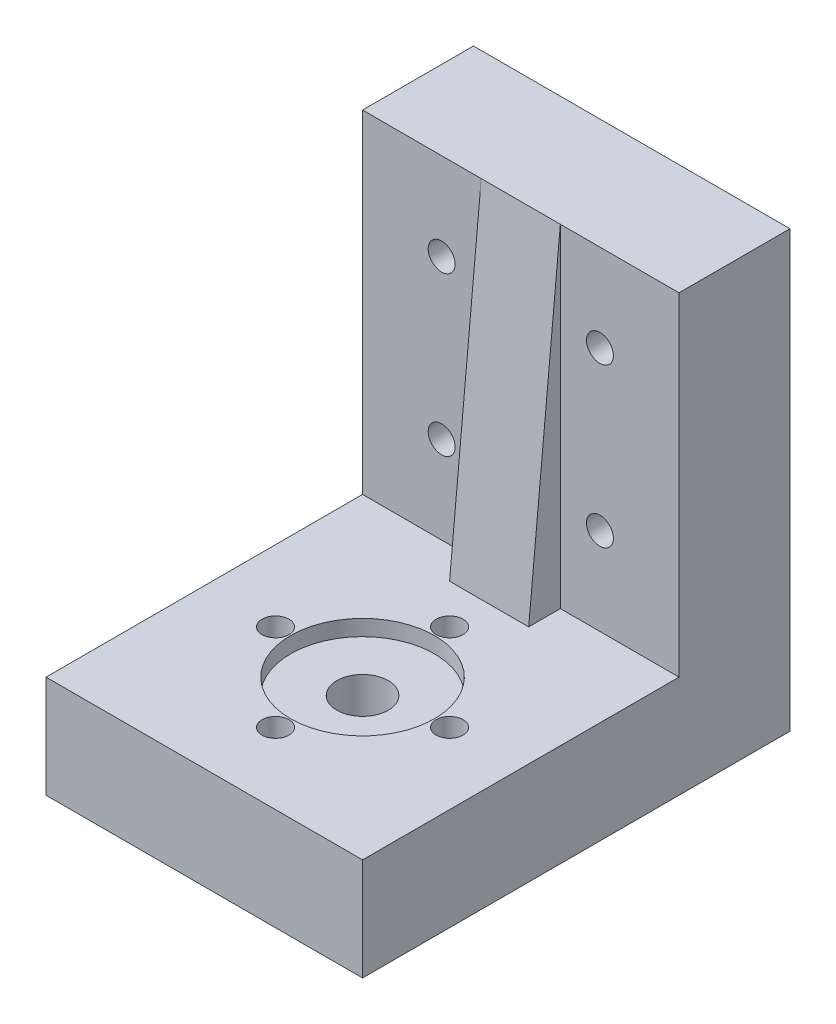
SolidWorks part; units mm, degrees
material "ABS"
ref_plane "Front Plane" through (0, 0, 0) normal (0, 0, 1) x (1, 0, 0)
ref_plane "Top Plane" through (0, 0, 0) normal (0, 1, 0) x (1, 0, 0)
ref_plane "Right Plane" through (0, 0, 0) normal (1, 0, 0) x (0, 0, -1)
sketch "Sketch1" plane through (0, 0, 0) normal (1, 0, 0) x (0, 0, -1)
  line L0 (24.9296, 27.1619) -> (24.9296, -27.8381)
  line L1 (24.9296, -27.8381) -> (-29.0904, -27.8381)
  line L2 (-29.0904, -27.8381) -> (-29.0904, -14.9081)
  line L3 (-29.0904, -14.9081) -> (10.9096, -14.9081)
  line L4 (10.9096, -14.9081) -> (10.9096, 27.1619)
  line L5 (10.9096, 27.1619) -> (24.9296, 27.1619)
  dimension "D1" = 55
  dimension "D2" = 14.02
  dimension "D3" = 12.93
  dimension "D4" = 40
extrude "Boss-Extrude1" add sketch "Sketch1" along normal mid plane 40
sketch "Sketch2" plane through (0, -14.9081, 0) normal (0, 1, 0) x (1, 0, 0)
  line L0 (20, -29.0904) -> (-20, -29.0904) construction
  circle A0 centre (0, -9.0904) radius 3.25
  dimension "D1" = 6.5
  dimension "D2" = 20
  dimension "D3" = 40
extrude "Cut-Extrude1" cut sketch "Sketch2" against normal through all contours A0
sketch "Sketch3" plane through (0, -14.9081, 0) normal (0, 1, 0) x (1, 0, 0)
  circle A0 centre (0, -9.0904) radius 9.1
  dimension "D1" = 18.2
extrude "Cut-Extrude2" cut sketch "Sketch3" against normal blind 2 contours A0
sketch "Sketch4" plane through (0, -14.9081, 0) normal (0, 1, 0) x (1, 0, 0)
  circle A0 centre (0, -9.0904) radius 11 construction
  circle A1 centre (0, 1.9096) radius 1.7
  circle A2 centre (11, -9.0904) radius 1.7
  circle A3 centre (0, -20.0904) radius 1.7
  circle A4 centre (-11, -9.0904) radius 1.7
  dimension "D1" = 22
  dimension "D2" = 3.4
  dimension "D3" = 4
extrude "Cut-Extrude3" cut sketch "Sketch4" against normal through all contours A1 | A2 | A3 | A4
sketch "Sketch5" plane through (0, 0, -10.9096) normal (0, 0, 1) x (1, 0, 0)
  line L0 (0, 27.1619) -> (0, -14.9081) construction
  line L1 (20, 27.1619) -> (-20, 27.1619) construction
  line L2 (20, -14.9081) -> (-20, -14.9081) construction
  line L3 (-20, 6.1269) -> (20, 6.1269) construction
  line L4 (-20, 27.1619) -> (-20, -14.9081) construction
  line L5 (20, 27.1619) -> (20, -14.9081) construction
  line L6 (20, -27.8381) -> (-20, -27.8381) construction
  line L7 (-10, -3.8731) -> (10, -3.8731) construction
  line L8 (-10, -3.8731) -> (-10, 16.1269) construction
  line L9 (-10, 16.1269) -> (10, 16.1269) construction
  line L10 (10, -3.8731) -> (10, 16.1269) construction
  line L11 (-10, -3.8731) -> (10, 16.1269) construction
  line L12 (-10, 16.1269) -> (10, -3.8731) construction
  circle A0 centre (-10, 16.1269) radius 1.7
  circle A1 centre (10, 16.1269) radius 1.7
  circle A2 centre (10, -3.8731) radius 1.7
  circle A3 centre (-10, -3.8731) radius 1.7
  point P12 (0, 6.1269)
  dimension "D3" = 3.4
  dimension "D6" = 25.665
  dimension "D7" = 23.965
  dimension "D1" = 20
  dimension "D2" = 20
  dimension "D4" = 2
  dimension "D5" = 2
extrude "Cut-Extrude4" cut sketch "Sketch5" against normal through all
ref_plane "Plane2" through (0, 0, 0) normal (-1, 0, 0) x (0, 0, 1)
sketch "Sketch15" plane through (0, 0, 0) normal (-1, 0, 0) x (0, 0, 1)
  line L0 (-10.9096, 27.1619) -> (-6.9096, -14.9081)
  line L1 (-10.9096, -14.9081) -> (29.0904, -14.9081) construction
  dimension "D1" = 4
  dimension "D2" = 42.07
rib "Rib26" sketch "Sketch15" sketch "Sketch15" thickness 10 extrusion direction parallel to sketch draft on no parameters "D1"=10
equation "\"Lb1\"= 40'beam length feature 1"
equation "\"b1\"= 40'width feature 1"
equation "\"p\"= 300'force"
equation "\"sf\"= 3'safety factor"
equation "\"Sy\"= 30'yield strength"
equation "\"L1\"= 18'moment arm feature 1"
equation "\"L2\"= 25.67 + \"L1\"'moment arm feature 2"
equation "\"E\"= 2000'modulus of elasticity"
equation "\"M1\"= \"p\" * \"L1\"'moment feature 1"
equation "\"M2\"= \"p\" * ( \"L2\" )'moment feature 2"
equation "\"dmax\"= .30'max deflection"
equation "\"h1\"= ( ( 6 * \"M1\" * ( \"Lb1\" ^ 2 ) ) / ( \"E\" * \"b1\" * \"dmax\" ) ) ^ ( 1 / 3 )'Thickness feature 1"
equation "\"b2\"= 40'width feature 2"
equation "\"Lb2\"= 55'beam length feature 2"
equation "\"h2\"= ( ( 6 * \"M2\" ) / ( \"b2\" * ( \"Sy\" / \"sf\" ) ) ) ^ ( 1 / 2 )'thickness feature 2"
equation "\"BoltD\"= 3.4'bolt clearance diameter"
equation "\"BoltCD\"= 22'bolt construction diameter"
equation "\"bossCD\"= 18.2'boss clearance diameter"
equation "\"shaftCD\"= 6.5'shaft clearance diameter"
equation "\"bossDepth\"= 2'boss depth"
equation "\"wallc\"= 20'wall construction square"
